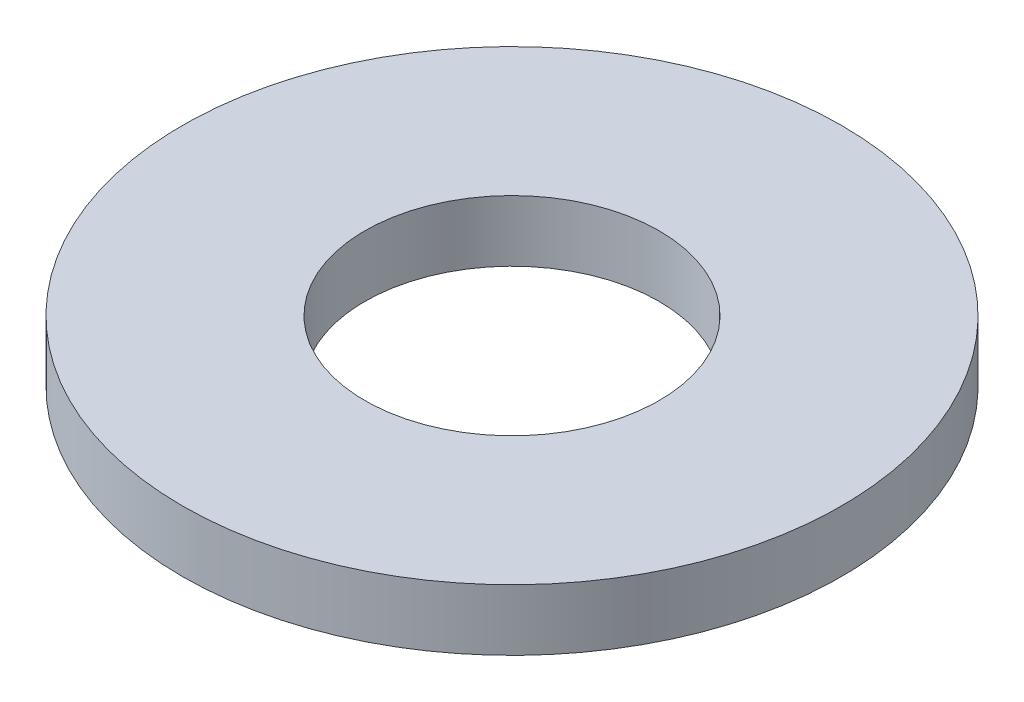
SolidWorks part; units mm, degrees
material "Cast Alloy Steel"
ref_plane "Front Plane" through (0, 0, 0) normal (0, 0, 1) x (1, 0, 0)
ref_plane "Top Plane" through (0, 0, 0) normal (0, 1, 0) x (1, 0, 0)
ref_plane "Right Plane" through (0, 0, 0) normal (1, 0, 0) x (0, 0, -1)
sketch "Sketch1" plane through (0, 0, 0) normal (0, 1, 0) x (1, 0, 0)
  circle A0 centre (0, 0) radius 3.9688
  circle A1 centre (0, 0) radius 8.89
  dimension "D1" = 7.9375
  dimension "D2" = 17.78
extrude "Boss-Extrude1" add sketch "Sketch1" along normal blind 1.651
